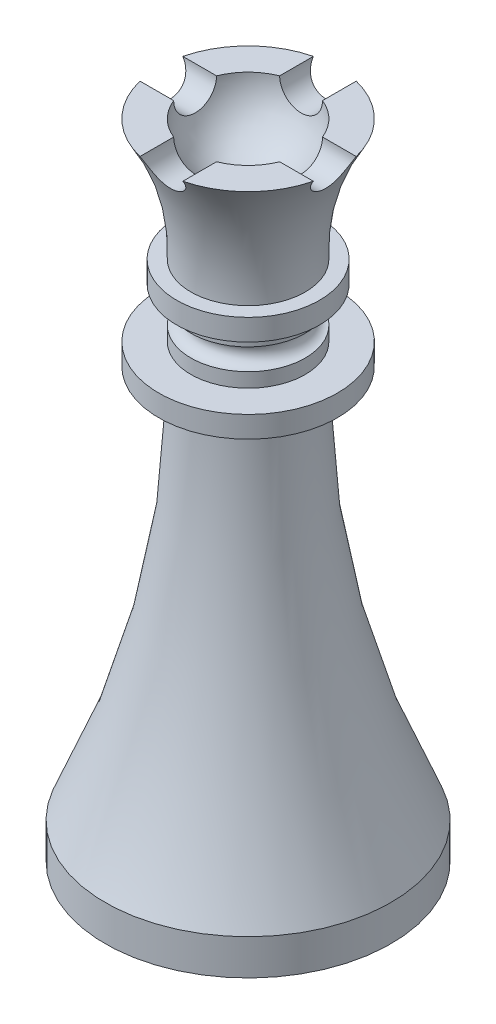
SolidWorks part; units mm, degrees
ref_plane "Front Plane" through (0, 0, 0) normal (0, 0, 1) x (1, 0, 0)
ref_plane "Top Plane" through (0, 0, 0) normal (0, 1, 0) x (1, 0, 0)
ref_plane "Right Plane" through (0, 0, 0) normal (1, 0, 0) x (0, 0, -1)
sketch "Sketch1" plane through (0, 0, 0) normal (0, 0, 1) x (1, 0, 0)
  line L0 (0, 0) -> (0, -88.5796) construction
  line L1 (0, 0) -> (0, 69.9455) construction
  line L2 (0, -60) -> (20, -60)
  line L3 (20, -60) -> (20, -55)
  line L4 (10.0087, 0) -> (12.5, 0)
  line L5 (12.5, 0) -> (12.5, 3)
  line L6 (12.5, 3) -> (8, 3)
  line L7 (8, 30) -> (12.5, 30)
  line L8 (10, 13) -> (8, 13)
  line L9 (8, 5) -> (8, 3)
  line L10 (8, 10) -> (10, 10)
  line L11 (0, 22) -> (0, -60)
  line L13 (10, 13) -> (10, 10)
  line L14 (8, 8) -> (8, 10)
  arc A0 (20, -55) -> (8.0088, -2.0243) centre (137.9992, -0.4456) cw
  arc A1 (8, 5) -> (8, 8) centre (8, 6.5) cw
  arc A2 (8, 13) -> (12.5, 30) centre (37.9776, 14.1604) cw
  arc A3 (0, 22) -> (8, 30) centre (0, 30) ccw
  arc A4 (10.0087, 0) -> (8.0088, -2.0243) centre (10.0087, -2) ccw
  dimension "D5" = 130
  dimension "D12" = 30
  dimension "D13" = 12.5
  dimension "D14" = 2
  dimension "D4" = 2
  dimension "D15" = 30
  dimension "D16" = 8
  dimension "D2" = 20
  dimension "D3" = 5
  dimension "D6" = 7
  dimension "D7" = 3
  dimension "D8" = 10
  dimension "D9" = 12.5
  dimension "D11" = 8
  dimension "D10" = 3
revolve "Revolve1" add sketch "Sketch1" angle 360 about L1
sketch "Sketch2" plane through (0, 0, 0) normal (0, 0, 1) x (1, 0, 0)
  line L0 (8, 30) -> (-8, 30) construction
  circle A0 centre (0, 30) radius 3
extrude "Cut-Extrude1" cut sketch "Sketch2" against normal up to next
pattern_circular "CirPattern1" count 4 over 360 about axis through (0, 13, 0) along (0, -1, 0) of "Cut-Extrude1"
scale "缩放比例1" scale about origin uniform scaling yes scale factor 0.6
